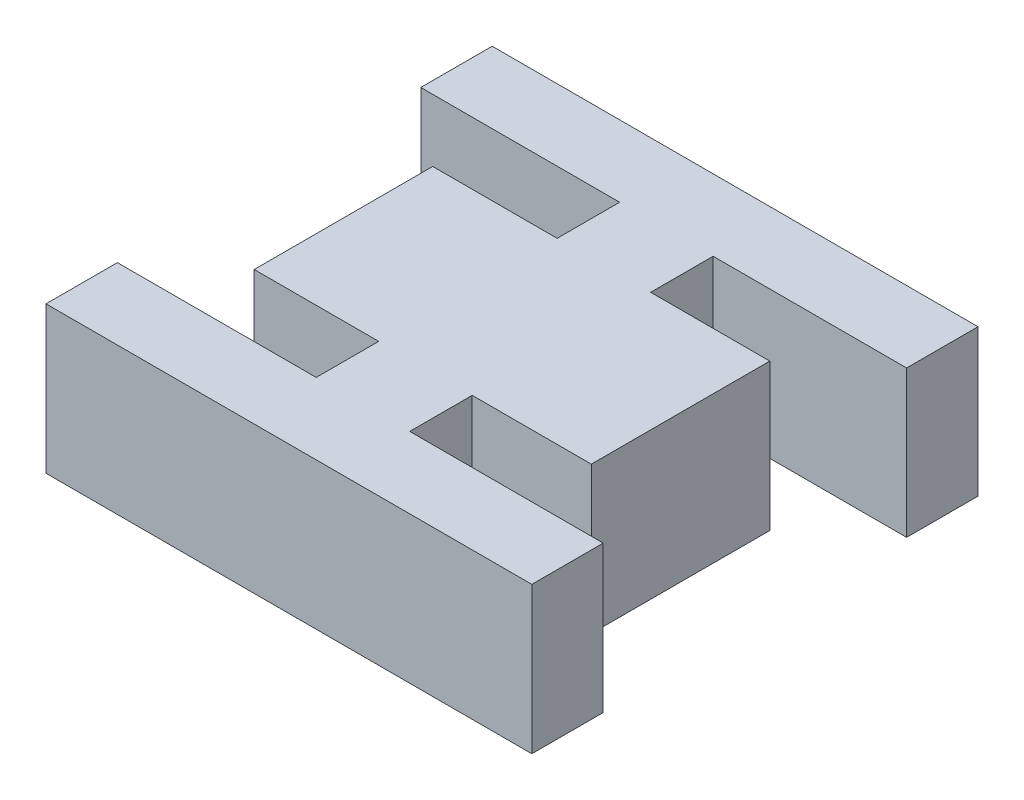
SolidWorks part; units mm, degrees
ref_plane "Plan de face" through (0, 0, 0) normal (0, 0, 1) x (1, 0, 0)
ref_plane "Plan de dessus" through (0, 0, 0) normal (0, 1, 0) x (1, 0, 0)
ref_plane "Plan de droite" through (0, 0, 0) normal (1, 0, 0) x (0, 0, -1)
sketch "Esquisse1" plane through (0, 0, 0) normal (0, 1, 0) x (1, 0, 0)
  line L0 (-122.5, 76.5) -> (-22.2263, 76.5)
  line L1 (-122.5, 112.5) -> (122.5, 112.5)
  line L2 (-122.5, 112.5) -> (-122.5, 76.5)
  line L3 (-122.5, -112.5) -> (122.5, -112.5)
  line L4 (122.5, 112.5) -> (122.5, 76.5)
  line L5 (-122.5, 112.5) -> (122.5, -112.5) construction
  line L6 (-122.5, -112.5) -> (122.5, 112.5) construction
  line L7 (-85, 45) -> (-22.2263, 45)
  line L8 (-85, 45) -> (-85, -45)
  line L9 (-85, -45) -> (-22.2263, -45)
  line L10 (85, 45) -> (85, -45)
  line L11 (-85, 45) -> (85, -45) construction
  line L12 (-85, -45) -> (85, 45) construction
  line L13 (122.5, -76.5) -> (24.9264, -76.5)
  line L14 (-122.5, -76.5) -> (-122.5, -112.5)
  line L15 (122.5, -76.5) -> (122.5, -112.5)
  line L16 (-22.2263, 76.5) -> (-22.2263, 45)
  line L17 (24.9264, 76.5) -> (24.9264, 45)
  line L18 (24.9264, -45) -> (24.9264, -76.5)
  line L19 (-22.2263, -45) -> (-22.2263, -76.5)
  line L20 (24.9264, -45) -> (85, -45)
  line L21 (-22.2263, -76.5) -> (-122.5, -76.5)
  line L22 (24.9264, 76.5) -> (122.5, 76.5)
  line L23 (24.9264, 45) -> (85, 45)
  point P0 (0, 0)
  point P6 (0, 0)
  dimension "D1" = 245
  dimension "D2" = 225
  dimension "D3" = 90
  dimension "D4" = 170
  dimension "D5" = 36
  dimension "D6" = 36
extrude "Boss.-Extru.1" add sketch "Esquisse1" along normal blind 74
